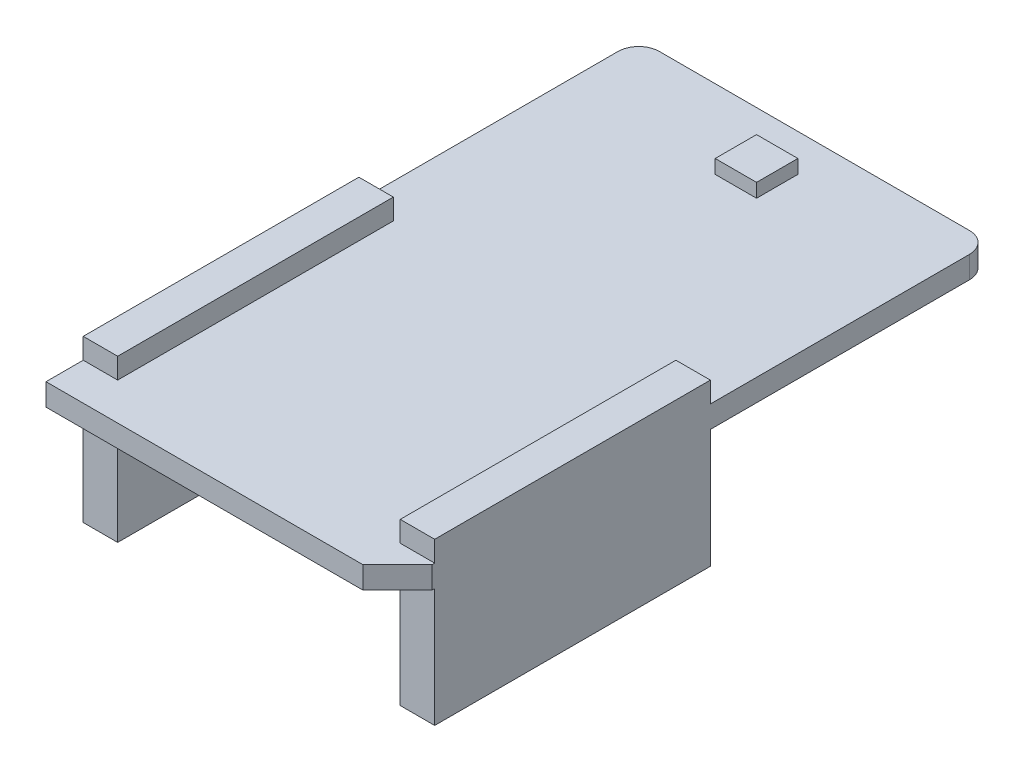
SolidWorks part; units mm, degrees
ref_plane "Front Plane" through (0, 0, 0) normal (0, 0, 1) x (1, 0, 0)
ref_plane "Top Plane" through (0, 0, 0) normal (0, 1, 0) x (1, 0, 0)
ref_plane "Right Plane" through (0, 0, 0) normal (1, 0, 0) x (0, 0, -1)
sketch "Sketch1" plane through (0, 0, 0) normal (0, 1, 0) x (1, 0, 0)
  line L1 (0, 0) -> (25.5, 0)
  line L2 (0, 0) -> (0, 43)
  line L3 (0, 43) -> (25.5, 43)
  line L4 (25.5, 0) -> (25.5, 43)
  line L5 (0, 0) -> (25.5, 43) construction
  line L6 (0, 43) -> (25.5, 0) construction
  point P4 (12.75, 21.5)
  dimension "D1" = 43
  dimension "D2" = 25.5
extrude "Boss-Extrude1" add sketch "Sketch1" along normal blind 1.6
sketch "Sketch2" plane through (0, 0, 0) normal (0, -1, 0) x (1, 0, 0)
  line L0 (12.75, 0) -> (12.75, -43) construction
  line L1 (0, 0) -> (25.5, 0) construction
  line L2 (25.5, -43) -> (0, -43) construction
  line L3 (0, -43) -> (0, 0) construction
  line L4 (0, -2.7) -> (2.5, -2.7)
  line L5 (0, -2.7) -> (0, -22.7)
  line L6 (0, -22.7) -> (2.5, -22.7)
  line L7 (2.5, -2.7) -> (2.5, -22.7)
  line L8 (0, -2.7) -> (2.5, -22.7) construction
  line L9 (0, -22.7) -> (2.5, -2.7) construction
  line L10 (25.5, -22.7) -> (23, -22.7)
  line L11 (23, -2.7) -> (23, -22.7)
  line L12 (25.5, -2.7) -> (23, -2.7)
  line L13 (25.5, -2.7) -> (25.5, -22.7)
  point P10 (1.25, -12.7)
  dimension "D1" = 2.7
  dimension "D2" = 20
  dimension "D3" = 2.5
extrude "Boss-Extrude2" add sketch "Sketch2" along normal blind 8.6 and the other way offset from surface (3.1 mm away) 1.5 other way up to face at (12.75, 1.6, -21.5)
sketch "Sketch3" plane through (0, 1.6, 0) normal (0, 1, 0) x (1, 0, 0)
  line L0 (12.75, 43) -> (12.75, 0) construction
  line L1 (25.5, 43) -> (0, 43) construction
  line L2 (0, 0) -> (25.5, 0) construction
  line L4 (11.25, 40.3) -> (14.25, 40.3)
  line L5 (11.25, 40.3) -> (11.25, 37.3)
  line L6 (11.25, 37.3) -> (14.25, 37.3)
  line L7 (14.25, 40.3) -> (14.25, 37.3)
  line L8 (11.25, 40.3) -> (14.25, 37.3) construction
  line L9 (11.25, 37.3) -> (14.25, 40.3) construction
  point P10 (12.75, 38.8)
  dimension "D1" = 3
  dimension "D2" = 2.7
extrude "Boss-Extrude3" add sketch "Sketch3" along normal blind 1
fillet "Fillet1" radius 1.5 2 edges at (25.5, 0.8, -43) (0, 0.8, -43)
chamfer "Chamfer1" distance 2.5 angle 45 1 edges at (25.5, 0.8, 0)
sketch "Sketch4" plane through (0, 2.6, 0) normal (0, 1, 0) x (1, 0, 0)
  line L0 (14.25, 40.3) -> (11.25, 37.3) construction
  point P4 (12.75, 38.8)
